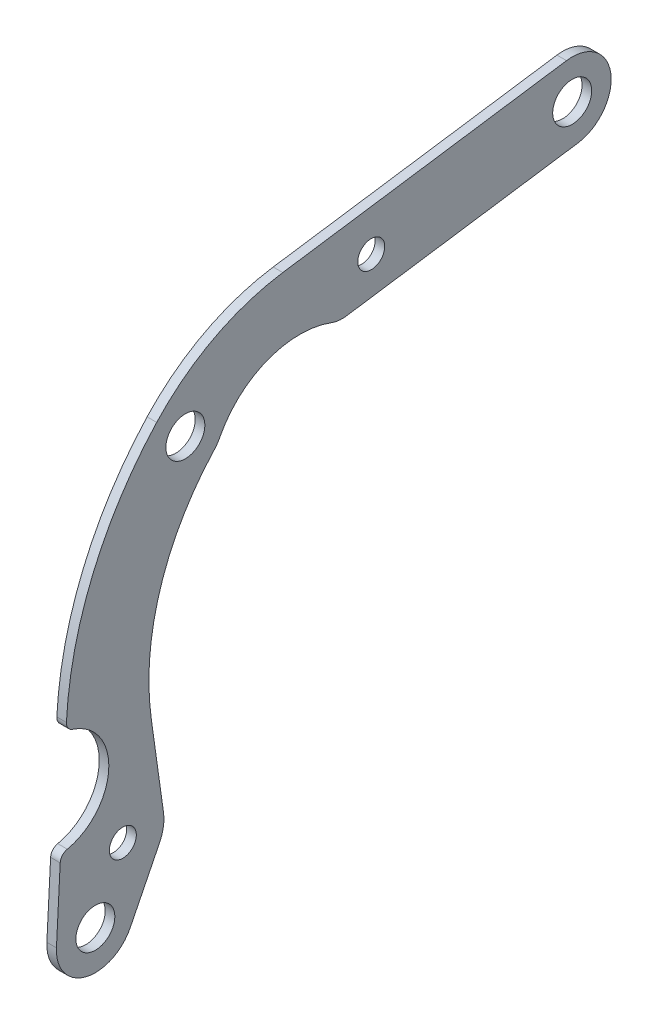
SolidWorks part; units mm, degrees
ref_plane "Front Plane" through (0, 0, 0) normal (0, 0, 1) x (1, 0, 0)
ref_plane "Top Plane" through (0, 0, 0) normal (0, 1, 0) x (1, 0, 0)
ref_plane "Right Plane" through (0, 0, 0) normal (1, 0, 0) x (0, 0, -1)
sketch "Sketch4" plane through (0, 0, 0) normal (1, 0, 0) x (0, 0, -1)
  line L1 (49.2357, 134.8726) -> (76.225, 138.8377) construction
  line L3 (62.5321, 158.0515) -> (157.2094, 171.961)
  line L4 (83.8046, 134.8976) -> (160.9886, 146.2371)
  line L5 (-12.9822, 0.6804) -> (-11.7283, 24.6061)
  line L6 (22.7453, 21.9054) -> (18.6604, 50.9709)
  line L8 (11.6362, -5.7965) -> (21.4406, 13.8852)
  line L9 (0, 0) -> (159.099, 159.099) construction
  line L10 (0, 0) -> (0, 169.8564) construction
  line L11 (-10.2334, 53.1304) -> (-8.2428, 91.114) construction
  line L12 (20.4622, 135.7972) -> (39.6003, 118.1979) construction
  arc A0 (78.8331, 135.4307) -> (41.5946, 121.0571) centre (68.2792, 107.3484) ccw
  arc A1 (18.6604, 50.9709) -> (39.6003, 118.1979) centre (100.2379, 62.4358) cw
  arc A2 (78.8331, 135.4307) -> (83.8046, 134.8976) centre (82.3511, 144.7914) ccw
  arc A3 (-9.6558, 64.152) -> (20.4622, 135.7972) centre (104.9002, 58.1483) cw
  arc A4 (11.6362, -5.7965) -> (-12.9822, 0.6804) centre (0, 0) cw
  arc A5 (41.5946, 121.0571) -> (39.6003, 118.1979) centre (30.0312, 126.9975) cw
  arc A7 (160.9886, 146.2371) -> (157.2094, 171.961) centre (159.099, 159.099) ccw
  circle A8 centre (0, 0) radius 13 construction
  arc A9 (-9.3569, 27.3834) -> (-7.5877, 61.142) centre (-13, 44.5) ccw
  circle A10 centre (-13, 44.5) radius 17.5 construction
  circle A11 centre (30.0312, 126.9975) radius 13 construction
  arc A12 (21.4406, 13.8852) -> (22.7453, 21.9054) centre (9.1705, 19.9975) ccw
  arc A13 (-7.5877, 61.142) -> (-9.6558, 64.152) centre (-6.6599, 63.9949) cw
  circle A14 centre (159.099, 159.099) radius 13 construction
  circle A16 centre (-13, 44.5) radius 16.5 construction
  arc A17 (-9.3569, 27.3834) -> (-11.7283, 24.6061) centre (-8.7324, 24.4491) ccw
  arc A18 (62.5321, 158.0515) -> (20.4622, 135.7972) centre (72.8838, 87.5905) ccw
  dimension "D1" = 26
  dimension "D2" = 26
  dimension "D3" = 26
  dimension "D5" = 33
  dimension "D7" = 60
  dimension "D10" = 10
  dimension "D14" = 3
  dimension "D15" = 3
  dimension "D16" = 22
  dimension "D17" = 133
  dimension "D18" = 225
  dimension "D8" = 45
  dimension "D11" = 8
  dimension "D22" = 13.7082
  dimension "D4" = 44.5
  dimension "D6" = 13
  dimension "D9" = 5
  dimension "D12" = 130.5
  dimension "D20" = 107
  dimension "D21" = 3
  dimension "D13" = 1
extrude "Extrude1" add sketch "Sketch4" along normal blind 3.2
sketch "Sketch5" plane through (0, 0, 0) normal (1, 0, 0) x (0, 0, -1)
  circle A0 centre (0, 0) radius 6.5
  circle A1 centre (159.099, 159.099) radius 6.5
  circle A2 centre (30.0312, 126.9975) radius 6.5
  circle A3 centre (30.0312, 126.9975) radius 13 construction
  dimension "D1" = 13
extrude "chassis mount holes" cut sketch "Sketch5" along normal through all
sketch "Sketch6" plane through (0, 0, 0) normal (1, 0, 0) x (0, 0, -1)
  line L0 (61.8805, 141.1018) -> (110.8752, 153.2877) construction
  line L2 (30.0312, 126.9975) -> (159.099, 159.099) construction
  circle A0 centre (9.1705, 19.9975) radius 4.5
  arc A1 (21.4406, 13.8852) -> (22.7453, 21.9054) centre (9.1705, 19.9975) ccw construction
  circle A2 centre (92.0499, 148.6055) radius 4.5
  dimension "D1" = 9
  dimension "D2" = 153
  dimension "D3" = 6
  dimension "D4" = 65.6751
  dimension "D5" = 67.0491
extrude "engine mount holes" cut sketch "Sketch6" along normal through all
